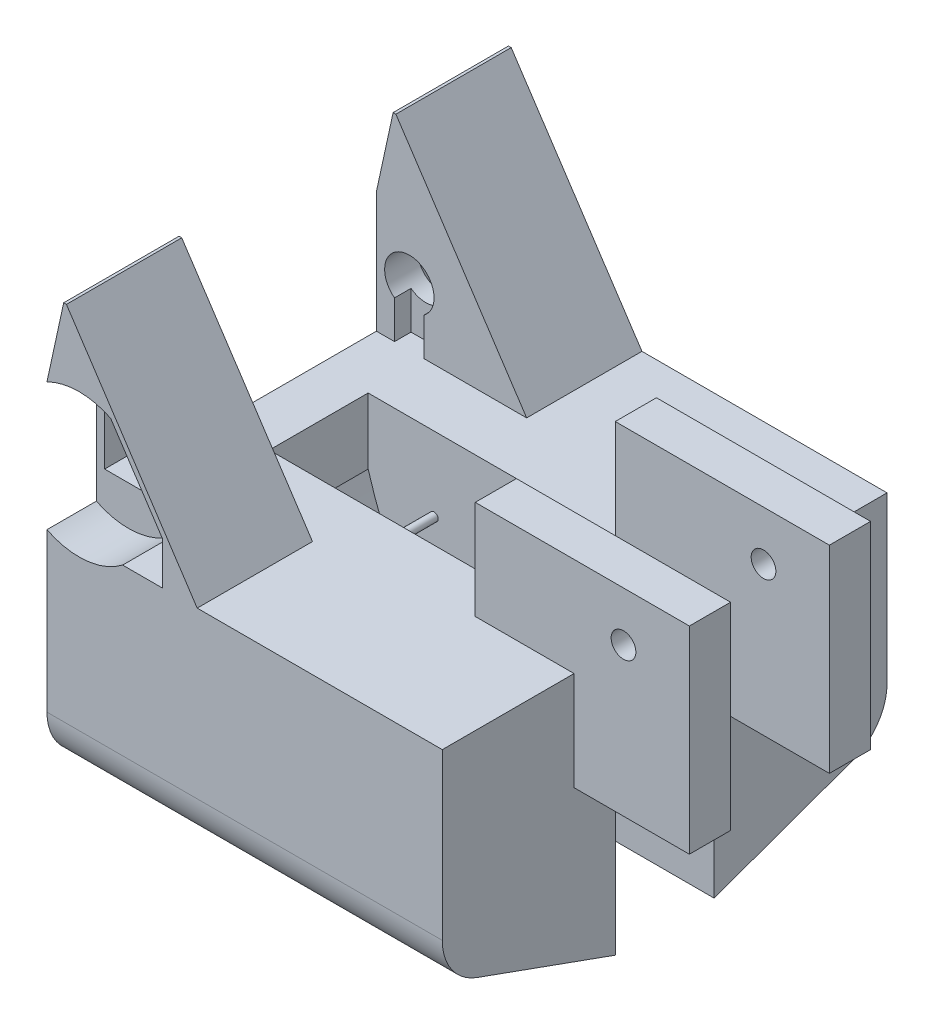
SolidWorks part; units mm, degrees
ref_plane "前视基准面" through (0, 0, 0) normal (0, 0, 1) x (1, 0, 0)
ref_plane "上视基准面" through (0, 0, 0) normal (0, 1, 0) x (1, 0, 0)
ref_plane "右视基准面" through (0, 0, 0) normal (1, 0, 0) x (0, 0, -1)
sketch "草图1" plane through (0, 0, 0) normal (1, 0, 0) x (0, 0, -1)
  line L0 (135, 0) -> (135, -170) construction
  line L1 (0, 0) -> (270, 0)
  line L2 (0, 0) -> (0, -100.2828)
  line L4 (270, 0) -> (270, -100.2828)
  line L5 (38.49, -136.6392) -> (62.3511, -70.3586) construction
  line L6 (21.17, -130.404) -> (127.5448, -168.6989) construction
  line L7 (142.4552, -168.6989) -> (248.83, -130.404) construction
  line L8 (58.2053, -81.8746) -> (-5.8219, -81.8746) construction
  line L9 (58.2053, -81.8746) -> (5.8219, -118.6911) construction
  line L10 (127.5448, -168.6989) -> (21.17, -130.404)
  line L11 (142.4552, -168.6989) -> (248.83, -130.404)
  line L12 (105.5031, -160.7639) -> (135, -78.8281) construction
  line L13 (135, -78.8281) -> (164.4969, -160.7639) construction
  arc A0 (0, -100.2828) -> (21.17, -130.404) centre (32.0136, -100.2828) ccw
  arc A1 (127.5448, -168.6989) -> (142.4552, -168.6989) centre (135, -147.9899) ccw
  arc A2 (270, -100.2828) -> (248.83, -130.404) centre (237.9864, -100.2828) cw
  dimension "D2" = 44.0202
  dimension "D3" = 170
  dimension "D1" = 270
  dimension "D4" = 32.0136
  dimension "D5" = 109.799
  dimension "D6" = 109.799
extrude "凸台-拉伸1" add sketch "草图1" along normal blind 30
sketch "草图2" plane through (30, 0, 0) normal (1, 0, 0) x (0, 0, -1)
  line L0 (135, 0) -> (135, -170) construction
  line L1 (270, 0) -> (0, 0) construction
  line L2 (135, -14.9009) -> (165, -14.9009) construction
  line L3 (165, 0) -> (165, -160.5828)
  line L4 (105, 0) -> (105, -160.5828)
  line L8 (0, 0) -> (0, -100.2828)
  line L9 (21.17, -130.404) -> (127.5448, -168.6989)
  line L10 (142.4552, -168.6989) -> (248.83, -130.404)
  line L11 (270, -100.2828) -> (270, 0)
  line L12 (270, 0) -> (0, 0)
  line L13 (0, 0) -> (0, -100.2828)
  line L14 (21.17, -130.404) -> (127.5448, -168.6989)
  line L15 (142.4552, -168.6989) -> (248.83, -130.404)
  line L16 (270, -100.2828) -> (270, 0)
  line L17 (270, 0) -> (0, 0)
  arc A0 (127.5448, -168.6989) -> (142.4552, -168.6989) centre (135, -147.9899) ccw construction
  arc A4 (0, -100.2828) -> (21.17, -130.404) centre (32.0136, -100.2828) ccw
  arc A5 (127.5448, -168.6989) -> (142.4552, -168.6989) centre (135, -147.9899) ccw
  arc A6 (248.83, -130.404) -> (270, -100.2828) centre (237.9864, -100.2828) ccw
  arc A7 (0, -100.2828) -> (21.17, -130.404) centre (32.0136, -100.2828) ccw
  arc A8 (127.5448, -168.6989) -> (142.4552, -168.6989) centre (135, -147.9899) ccw
  arc A9 (248.83, -130.404) -> (270, -100.2828) centre (237.9864, -100.2828) ccw
  line M12 (0, 0) -> (0, -100.2828)
  arc M13 (0, -100.2828) -> (21.17, -130.404) centre (32.0136, -100.2828) ccw
  line M14 (21.17, -130.404) -> (127.5448, -168.6989)
  line M16 (142.4552, -168.6989) -> (248.83, -130.404)
  arc M17 (248.83, -130.404) -> (270, -100.2828) centre (237.9864, -100.2828) ccw
  line M18 (270, -100.2828) -> (270, 0)
  line M19 (270, 0) -> (0, 0)
  dimension "D1" = 30
  dimension "D2" = 0
extrude "凸台-拉伸2" add sketch "草图2" along normal blind 210 contours L4 M19 M12 M13 M14 | L3 M19 M16 M17 M18
sketch "草图6" plane through (0, 0, -105) normal (0, 0, -1) x (-1, 0, 0)
  line L0 (-71.1167, 0) -> (-71.1167, -409.9146) construction
  line L8 (-30, -160.5828) -> (-30, 0)
  line L9 (-30, 0) -> (-240, 0)
  line L12 (-240, 0) -> (-240, -160.5828)
  line L13 (-240, -160.5828) -> (-30, -160.5828)
  line L15 (-30, -160.5828) -> (-30, 0)
  line L16 (-30, 0) -> (-240, 0)
  line L19 (-240, 0) -> (-240, -160.5828)
  line L20 (-240, -160.5828) -> (-30, -160.5828)
  dimension "D2" = 41.1167
  dimension "D1" = 0
sketch "草图8" plane through (240, 0, 0) normal (1, 0, 0) x (0, 0, -1)
  line L0 (105, 0) -> (105, -160.5828) construction
  line L1 (105, -60) -> (80, -60)
  line L2 (105, -60) -> (105, 60)
  line L3 (105, 60) -> (80, 60)
  line L4 (80, -60) -> (80, 60)
  line L5 (105, -60) -> (80, 60) construction
  line L6 (105, 60) -> (80, -60) construction
  line L7 (135, 0) -> (135, -208.0575) construction
  line L8 (165, 0) -> (105, 0) construction
  line L9 (105, 0) -> (0, 0) construction
  line L10 (165, 60) -> (190, -60) construction
  line L11 (165, -60) -> (190, 60) construction
  line L12 (190, -60) -> (190, 60)
  line L13 (165, 60) -> (190, 60)
  line L14 (165, -60) -> (165, 60)
  line L15 (165, -60) -> (190, -60)
  point P4 (92.5, 0)
  point P17 (177.5, 0)
  dimension "D1" = 25
  dimension "D2" = 60
  dimension "D3" = 60
extrude "凸台-拉伸5" add sketch "草图8" along normal blind 70
sketch "草图9" plane through (240, 0, 0) normal (-1, 0, 0) x (0, 0, 1)
  line L4 (-105, 60) -> (-105, 0)
  line L5 (-105, 0) -> (-80, 0)
  line L6 (-80, 0) -> (-80, 60)
  line L7 (-80, 60) -> (-105, 60)
  line L8 (-105, 60) -> (-105, 0)
  line L9 (-105, 0) -> (-80, 0)
  line L10 (-80, 0) -> (-80, 60)
  line L11 (-80, 60) -> (-105, 60)
  line L12 (-190, 0) -> (-165, 0)
  line L13 (-165, 0) -> (-165, 60)
  line L14 (-165, 60) -> (-190, 60)
  line L15 (-190, 60) -> (-190, 0)
  line L16 (-190, 0) -> (-165, 0)
  line L17 (-165, 0) -> (-165, 60)
  line L18 (-165, 60) -> (-190, 60)
  line L19 (-190, 60) -> (-190, 0)
  dimension "D1" = 0
  dimension "D2" = 0
extrude "凸台-拉伸6" add sketch "草图9" along normal blind 60
sketch "草图10" plane through (0, 0, -80) normal (0, 0, 1) x (1, 0, 0)
  line L0 (240, 0) -> (240, 31.0013) construction
  line L2 (180, 30) -> (270, 30) construction
  line L3 (180, 0) -> (180, 60) construction
  circle A0 centre (270, 30) radius 7.5
  dimension "D2" = 15
  dimension "D1" = 30
extrude "切除-拉伸3" cut sketch "草图10" against normal through all
sketch "草图11" plane through (0, 0, -105) normal (0, 0, -1) x (-1, 0, 0)
  line L0 (0, 0) -> (0, 80.2418) construction
  line L1 (-240, -160.5828) -> (-124.1295, -160.5828) construction
  line L2 (-124.1295, -160.5828) -> (-108.2032, -160.5828) construction
  line L3 (-30, 0) -> (-30, -40) construction
  line L4 (-30, -40) -> (-30, -160.5828)
  line L5 (-30, -160.5828) -> (-108.2032, -160.5828)
  circle A0 centre (-270, 30) radius 240 construction
  arc A1 (-108.2032, -160.5828) -> (-30, -40) centre (-270, 30) ccw
  circle A2 centre (-270, 30) radius 250 construction
  dimension "D1" = 480
  dimension "D2" = 10
extrude "凸台-拉伸7" add sketch "草图11" along normal blind 60
sketch "草图12" plane through (0, 0, -165) normal (0, 0, 1) x (1, 0, 0)
  line L0 (30, 0) -> (240, 0) construction
  line L1 (70, -45) -> (70, 0) construction
  line L4 (30, -160.5828) -> (30, 0) construction
  circle A0 centre (70, -45) radius 2.5
  dimension "D3" = 5
  dimension "D4" = 45
  dimension "D1" = 45
  dimension "D2" = 40
extrude "凸台-拉伸8" add sketch "草图12" along normal through all
sketch "草图13" plane through (0, 0, 0) normal (0, 1, 0) x (1, 0, 0)
  line L0 (0, 270) -> (0, 240.5719) construction
  line L1 (0, 270) -> (0, 0) construction
  line L2 (0, 240.5719) -> (0, 192.1942) construction
sketch "草图14" plane through (0, 0, 0) normal (0, 1, 0) x (1, 0, 0)
  line L0 (0, 250) -> (0, 200)
  line L1 (0, 250) -> (125, 250)
  line L2 (0, 200) -> (125, 200)
  line L3 (125, 250) -> (125, 200)
  line L4 (0, 270) -> (0, 0) construction
  line L5 (240, 270) -> (0, 270) construction
  line L6 (0, 135) -> (52.375, 135) construction
  line L7 (125, 20) -> (125, 70)
  line L8 (0, 70) -> (125, 70)
  line L9 (0, 20) -> (125, 20)
  line L10 (0, 20) -> (0, 70)
  dimension "D1" = 20
  dimension "D2" = 50
  dimension "D3" = 125
extrude "凸台-拉伸9" add sketch "草图14" along normal blind 120
sketch "草图15" plane through (0, 0, -20) normal (0, 0, 1) x (1, 0, 0)
  line L0 (0, 120) -> (0, 0) construction
  line L1 (0, 70) -> (70, 70)
  line L2 (0, 70) -> (0, 0)
  line L3 (0, 0) -> (70, 0)
  line L4 (70, 70) -> (70, 0)
  line L5 (0, 120) -> (125, 120) construction
  dimension "D1" = 70
  dimension "D2" = 70
  dimension "D3" = 50
extrude "切除-拉伸4" cut sketch "草图15" against normal blind 10
sketch "草图16" plane through (0, 0, -30) normal (0, 0, 1) x (1, 0, 0)
  line L0 (0, 35) -> (70, 35) construction
  line L1 (0, 70) -> (0, 0) construction
  line L2 (70, 0) -> (70, 70) construction
  line L3 (0, 35) -> (35, 35) construction
  line L4 (35, 70) -> (35, 0) construction
  line L5 (35, 35) -> (35, 15)
  line L6 (70, 70) -> (0, 70) construction
  line L7 (0, 35) -> (35, 35) construction
  line L8 (0, 0) -> (70, 0) construction
  line L9 (35, 35) -> (35, 55) construction
  line L10 (35, 55) -> (5, 55) construction
  line L11 (35, 35) -> (35, 55)
  line L12 (35, 55) -> (5, 55)
  line L13 (5, 55) -> (5, 15)
  line L14 (35, 15) -> (5, 15)
  point P21 (5, 35)
  dimension "D1" = 35
  dimension "D2" = 20
  dimension "D3" = 30
extrude "切除-拉伸5" cut sketch "草图16" against normal blind 20 contours L14 L5 L11 L12 L13
sketch "草图17" plane through (0, 0, -30) normal (0, 0, 1) x (1, 0, 0)
  line L0 (35, 35) -> (19.5, 34.5) construction
  line L1 (35, 55) -> (35, 15) construction
  circle A0 centre (19.5, 34.5) radius 43.4713
extrude "切除-拉伸6" cut sketch "草图17" along normal through all
sketch "草图18" plane through (0, 0, -20) normal (0, 0, 1) x (1, 0, 0)
  line L0 (0, 73.3523) -> (11.8199, 120) construction
  line L1 (0, 73.3523) -> (0, -4.3523) construction
  line L2 (0, 120) -> (125, 120) construction
  line L3 (11.8199, 120) -> (62.5, 43.3973) construction
  line L4 (62.5, 43.3973) -> (91.2115, 0) construction
  line L5 (11.8199, 120) -> (91.2115, 0)
  line L6 (91.2115, 0) -> (87.3179, 0)
  line L7 (70, 0) -> (125, 0) construction
  line L8 (87.3179, 0) -> (10.7417, 115.7446)
  line L9 (10.7417, 115.7446) -> (11.8199, 120)
  arc A0 (44.5899, 70) -> (0, 73.3523) centre (19.5, 34.5) ccw construction
extrude "凸台-拉伸10" add sketch "草图18" along normal blind 20
sketch "草图19" plane through (0, 0, -20) normal (0, 0, 1) x (1, 0, 0)
  line L0 (10.856, 115.5717) -> (11.8199, 120)
  line L1 (10.7417, 115.7446) -> (87.3179, 0) construction
  line L2 (11.8199, 120) -> (10.7417, 115.7446) construction
  line L3 (11.8199, 120) -> (125, 120) construction
  line L4 (11.8199, 120) -> (0, 65.6972)
  line L5 (0, 73.3523) -> (0, -4.3523) construction
  line L6 (0, 65.6972) -> (0, 73.3523)
  line L7 (0, 120) -> (0, 73.3523) construction
  line L8 (0, 73.3523) -> (10.1537, 120)
  line L9 (0, 120) -> (11.8199, 120) construction
  line L10 (10.1537, 120) -> (11.8199, 120)
  line L11 (10.1537, 120) -> (11.8199, 120)
  line M2 (38.6846, 73.509) -> (10.7417, 115.7446)
  line M3 (10.7417, 115.7446) -> (11.8199, 120)
  line M4 (11.8199, 120) -> (0, 120)
  arc M6 (0, 73.3523) -> (38.6846, 73.509) centre (19.5, 34.5) cw
extrude "凸台-拉伸11" add sketch "草图19" along normal blind 20 contours L8 L4 M6 M2 M3 M4
sketch "草图20" plane through (0, 0, -20) normal (0, 0, 1) x (1, 0, 0)
  line L3 (0, 120) -> (0, 73.3523)
  line L4 (0, 73.3523) -> (10.1537, 120)
  line L5 (10.1537, 120) -> (0, 120)
  line L6 (0, 120) -> (0, 73.3523)
  line L7 (0, 73.3523) -> (10.1537, 120)
  line L8 (10.1537, 120) -> (0, 120)
  point P2 (0, 0)
  point P4 (0, 0)
  dimension "D1" = 0
extrude "切除-拉伸7" cut sketch "草图20" against normal through all
sketch "草图22" plane through (0, 0, -20) normal (0, 0, 1) x (1, 0, 0)
  line L0 (44.8997, 70) -> (70, 32.0611)
  line L7 (70, 32.0611) -> (91.2115, 0)
  line L8 (91.2115, 0) -> (125, 0)
  line L9 (125, 0) -> (125, 120)
  line L10 (125, 120) -> (11.8199, 120)
  line L11 (11.8199, 120) -> (44.8997, 70)
  line L12 (44.8997, 70) -> (70, 70)
  line L13 (70, 70) -> (70, 32.0611)
  line L14 (70, 32.0611) -> (91.2115, 0)
  line L15 (91.2115, 0) -> (125, 0)
  line L16 (125, 0) -> (125, 120)
  line L17 (125, 120) -> (11.8199, 120)
  line L18 (11.8199, 120) -> (44.8997, 70)
  dimension "D1" = 0
extrude "切除-拉伸8" cut sketch "草图22" against normal through all
sketch "草图23" plane through (0, 0, 0) normal (0, 0, 1) x (1, 0, 0)
  line L0 (87.3179, 0) -> (91.2115, 0)
  line L10 (0, -4.3523) -> (0, -100.2828)
  line L11 (0, -100.2828) -> (240, -100.2828)
  line L12 (240, -100.2828) -> (240, 0)
  line L13 (240, 0) -> (91.2115, 0)
  line L14 (91.2115, 0) -> (11.8199, 120)
  line L15 (11.8199, 120) -> (10.1537, 120)
  line L16 (10.1537, 120) -> (0, 73.3523)
  line L17 (1.8573, 74.2302) -> (10.856, 115.5717)
  line L18 (10.856, 115.5717) -> (87.3179, 0)
  line L19 (87.3179, 0) -> (45.9481, 0)
  line L20 (0, -4.3523) -> (0, -100.2828)
  line L21 (0, -100.2828) -> (240, -100.2828)
  line L22 (240, -100.2828) -> (240, 0)
  line L23 (240, 0) -> (91.2115, 0)
  line L24 (91.2115, 0) -> (11.8199, 120)
  line L25 (11.8199, 120) -> (10.1537, 120)
  line L26 (10.1537, 120) -> (0, 73.3523)
  line L27 (1.8573, 74.2302) -> (10.856, 115.5717)
  line L28 (10.856, 115.5717) -> (87.3179, 0)
  line L29 (87.3179, 0) -> (45.9481, 0)
  arc A2 (0, -4.3523) -> (45.9481, 0) centre (19.5, 34.5) ccw
  arc A3 (1.8573, 74.2302) -> (0, 73.3523) centre (19.5, 34.5) ccw
  arc A4 (0, -4.3523) -> (45.9481, 0) centre (19.5, 34.5) ccw
  arc A5 (1.8573, 74.2302) -> (0, 73.3523) centre (19.5, 34.5) ccw
  line M18 (91.2115, 0) -> (11.8199, 120)
  line M19 (11.8199, 120) -> (10.1537, 120)
  line M20 (10.1537, 120) -> (0, 73.3523)
  arc M21 (0, 73.3523) -> (1.8573, 74.2302) centre (19.5, 34.5) cw
  line M22 (1.8573, 74.2302) -> (10.856, 115.5717)
  line M23 (10.856, 115.5717) -> (87.3179, 0)
  dimension "D1" = 0
extrude "凸台-拉伸19" add sketch "草图23" against normal up to next contours L0 M23 M18 M19 M20 M21 M22
sketch "草图24" plane through (0, 0, -20) normal (0, 0, 1) x (1, 0, 0)
  line L3 (87.3179, 0) -> (70, 26.1759)
  line L4 (70, 26.1759) -> (70, 0)
  line L5 (70, 0) -> (87.3179, 0)
  line L6 (87.3179, 0) -> (70, 26.1759)
  line L7 (70, 26.1759) -> (70, 0)
  line L8 (70, 0) -> (87.3179, 0)
  dimension "D1" = 0
extrude "凸台-拉伸20" add sketch "草图24" along normal up to vertex (20 mm away)
sketch "草图25" plane through (0, 0, -20) normal (0, 0, 1) x (1, 0, 0)
  line L2 (38.6846, 73.509) -> (10.856, 115.5717)
  line L3 (10.856, 115.5717) -> (1.8573, 74.2302)
  line L4 (38.6846, 73.509) -> (10.856, 115.5717)
  line L5 (10.856, 115.5717) -> (1.8573, 74.2302)
  arc A1 (38.6846, 73.509) -> (1.8573, 74.2302) centre (19.5, 34.5) ccw
  arc A2 (38.6846, 73.509) -> (1.8573, 74.2302) centre (19.5, 34.5) ccw
  dimension "D1" = 0
extrude "凸台-拉伸21" add sketch "草图25" along normal blind 20
sketch "草图26" plane through (0, 0, -250) normal (0, 0, -1) x (-1, 0, 0)
  line L10 (-70, 26.1759) -> (-38.6846, 73.509)
  line L11 (-70, 0) -> (-70, 26.1759)
  line L12 (-45.9481, 0) -> (-70, 0)
  line L13 (0, -100.2828) -> (0, -4.3523)
  line L14 (-240, -100.2828) -> (0, -100.2828)
  line L15 (-240, 0) -> (-240, -100.2828)
  line L16 (-91.2115, 0) -> (-240, 0)
  line L17 (-11.8199, 120) -> (-91.2115, 0)
  line L18 (-10.1537, 120) -> (-11.8199, 120)
  line L19 (0, 73.3523) -> (-10.1537, 120)
  line L20 (-70, 26.1759) -> (-38.6846, 73.509)
  line L21 (-70, 0) -> (-70, 26.1759)
  line L22 (-45.9481, 0) -> (-70, 0)
  line L23 (0, -100.2828) -> (0, -4.3523)
  line L24 (-240, -100.2828) -> (0, -100.2828)
  line L25 (-240, 0) -> (-240, -100.2828)
  line L26 (-91.2115, 0) -> (-240, 0)
  line L27 (-11.8199, 120) -> (-91.2115, 0)
  line L28 (-10.1537, 120) -> (-11.8199, 120)
  line L29 (0, 73.3523) -> (-10.1537, 120)
  arc A2 (0, 73.3523) -> (-38.6846, 73.509) centre (-19.5, 34.5) ccw
  arc A3 (-45.9481, 0) -> (0, -4.3523) centre (-19.5, 34.5) ccw
  arc A4 (0, 73.3523) -> (-38.6846, 73.509) centre (-19.5, 34.5) ccw
  arc A5 (-45.9481, 0) -> (0, -4.3523) centre (-19.5, 34.5) ccw
  dimension "D1" = 0
extrude "凸台-拉伸22" add sketch "草图26" along normal blind 20
sketch "草图27" plane through (0, 0, -270) normal (0, 0, -1) x (-1, 0, 0)
  line L4 (-38.6846, 73.509) -> (-70, 26.1759)
  line L5 (0, -4.3523) -> (0, 73.3523)
  line L6 (-70, 0) -> (-45.9481, 0)
  line L7 (-70, 26.1759) -> (-70, 0)
  line L8 (-38.6846, 73.509) -> (-70, 26.1759)
  line L9 (0, -4.3523) -> (0, 73.3523)
  line L10 (-70, 0) -> (-45.9481, 0)
  line L11 (-70, 26.1759) -> (-70, 0)
  arc A2 (0, 73.3523) -> (-38.6846, 73.509) centre (-19.5, 34.5) ccw
  arc A3 (-45.9481, 0) -> (0, -4.3523) centre (-19.5, 34.5) ccw
  arc A4 (0, 73.3523) -> (-38.6846, 73.509) centre (-19.5, 34.5) ccw
  arc A5 (-45.9481, 0) -> (0, -4.3523) centre (-19.5, 34.5) ccw
  dimension "D1" = 0
extrude "切除-拉伸9" cut sketch "草图27" against normal blind 30
sketch "草图29" plane through (0, 0, -70) normal (0, 0, -1) x (-1, 0, 0)
  line L0 (-5, 55) -> (-35, 15) construction
  line L1 (-5, 15) -> (-35, 55) construction
  line L4 (-35, 15) -> (-5, 15)
  line L5 (-35, 55) -> (-35, 15)
  line L6 (-5, 55) -> (-35, 55)
  line L7 (-5, 15) -> (-5, 55)
  line L8 (-35, 15) -> (-5, 15) construction
  line L9 (-35, 55) -> (-35, 15) construction
  line L10 (-5, 55) -> (-35, 55) construction
  line L11 (-5, 15) -> (-5, 55) construction
  circle A0 centre (-20, 35) radius 15
  dimension "D2" = 30
  dimension "D1" = 0
extrude "切除-拉伸11" cut sketch "草图29" against normal through all both and the other way through all
sketch "草图30" plane through (30, 0, 0) normal (1, 0, 0) x (0, 0, -1)
  line L3 (142.4552, -168.6989) -> (165, -160.5828)
  line L4 (165, -160.5828) -> (105, -160.5828)
  line L5 (105, -160.5828) -> (127.5448, -168.6989)
  line L6 (142.4552, -168.6989) -> (165, -160.5828)
  line L7 (165, -160.5828) -> (105, -160.5828)
  line L8 (105, -160.5828) -> (127.5448, -168.6989)
  arc A1 (127.5448, -168.6989) -> (142.4552, -168.6989) centre (135, -147.9899) ccw
  arc A2 (127.5448, -168.6989) -> (142.4552, -168.6989) centre (135, -147.9899) ccw
  dimension "D1" = 0
extrude "凸台-拉伸23" add sketch "草图30" along normal up to vertex (78.2032 mm away) up to point (108.2032, -160.5828, -165)
sketch "草图33" plane through (0, 0, -240) normal (0, 0, -1) x (-1, 0, 0)
  line L0 (-35, 15) -> (-5, 15) construction
  line L1 (-35, 55) -> (-35, 15) construction
  line L2 (-35, 55) -> (-5, 55) construction
  line L3 (-5, 55) -> (-5, 15) construction
  line L4 (-35, 15) -> (-5, 15)
  line L5 (-35, 55) -> (-35, 15)
  line L6 (-35, 55) -> (-5, 55)
  line L7 (-5, 55) -> (-5, 15)
extrude "切除-拉伸14" cut sketch "草图33" against normal blind 20
sketch "草图34" plane through (0, 0, -200) normal (0, 0, 1) x (1, 0, 0)
  line L0 (20, 50) -> (20, 2.4606) construction
  line L1 (11, 0) -> (11, 35.3006)
  line L2 (11, 0) -> (29, 0)
  line L3 (11, 35.3006) -> (29, 35.3006)
  line L4 (29, 0) -> (29, 35.3006)
  line L5 (11, 0) -> (29, 35.3006) construction
  line L6 (11, 35.3006) -> (29, 0) construction
  line L7 (0, 0) -> (91.2115, 0) construction
  arc A0 (35, 35) -> (5, 35) centre (20, 35) ccw construction
  point P6 (14.8133, 0)
  point P7 (20, 17.6503)
  point P14 (0, 0)
  point P15 (0, 0)
  dimension "D1" = 18
extrude "切除-拉伸15" cut sketch "草图34" against normal blind 10
sketch "草图35" plane through (0, 0, -70) normal (0, 0, -1) x (-1, 0, 0)
  line L3 (-11, 0) -> (-11, 23)
  line L4 (-29, 0) -> (-11, 0)
  line L5 (-29, 23) -> (-29, 0)
  line L6 (-11, 0) -> (-11, 23)
  line L7 (-29, 0) -> (-11, 0)
  line L8 (-29, 23) -> (-29, 0)
  arc A1 (-29, 23) -> (-11, 23) centre (-20, 35) ccw
  arc A2 (-29, 23) -> (-11, 23) centre (-20, 35) ccw
  dimension "D1" = 0
extrude "切除-拉伸16" cut sketch "草图35" against normal blind 10
sketch "草图36" plane through (0, 0, 0) normal (-1, 0, 0) x (0, 0, 1)
  line L0 (-235.6917, -100.008) -> (-211.6417, -100.008) construction
  line L1 (-135, -147.9899) -> (-135, -104.794) construction
  line L2 (-34.3083, -100.008) -> (-58.3583, -100.008) construction
  circle A0 centre (-235.6917, -100.008) radius 15.9
  circle A1 centre (-34.3083, -100.008) radius 15.9
  ellipse E0 centre (-235.6917, -100.008) end of major axis (-211.6417, -100.008) minor radius 15.9
  ellipse E1 centre (-34.3083, -100.008) end of major axis (-58.3583, -100.008) minor radius 15.9
  dimension "D2" = 31.8
  dimension "D1" = 24.05
extrude "切除-拉伸17" cut sketch "草图36" against normal blind 4 contours A0 E0 | A0 | A0 E0 | E1 A1 | A1 | E1 A1
